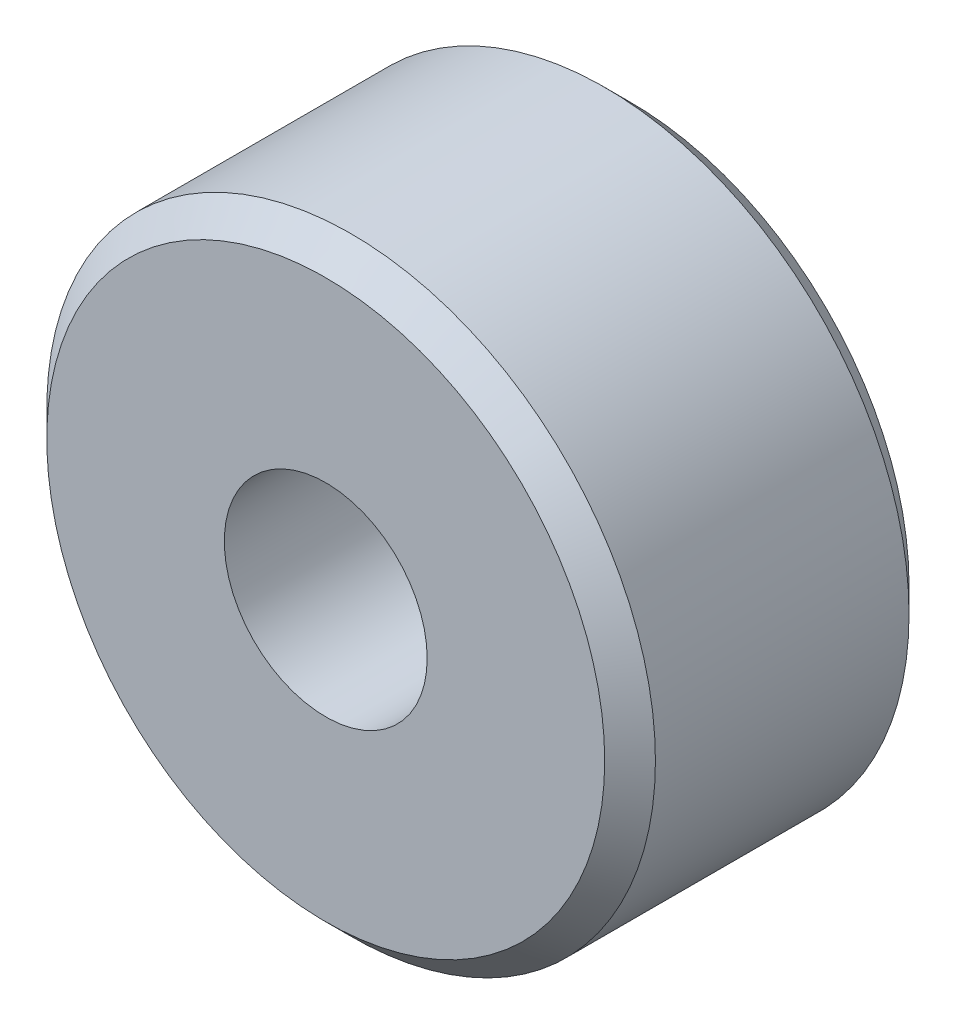
SolidWorks part; units mm, degrees
ref_plane "Front Plane" through (0, 0, 0) normal (0, 0, 1) x (1, 0, 0)
ref_plane "Top Plane" through (0, 0, 0) normal (0, 1, 0) x (1, 0, 0)
ref_plane "Right Plane" through (0, 0, 0) normal (1, 0, 0) x (0, 0, -1)
sketch "Sketch1" plane through (0, 0, 0) normal (0, 0, 1) x (1, 0, 0)
  circle A0 centre (0, 0) radius 1
  dimension "D1" = 2
extrude "Extrude-Thin1" add sketch "Sketch1" along normal blind 3 thin
chamfer "Chamfer1" distance 0.25 angle 45 2 edges at (3, 0, 0) (3, 0, 3)
